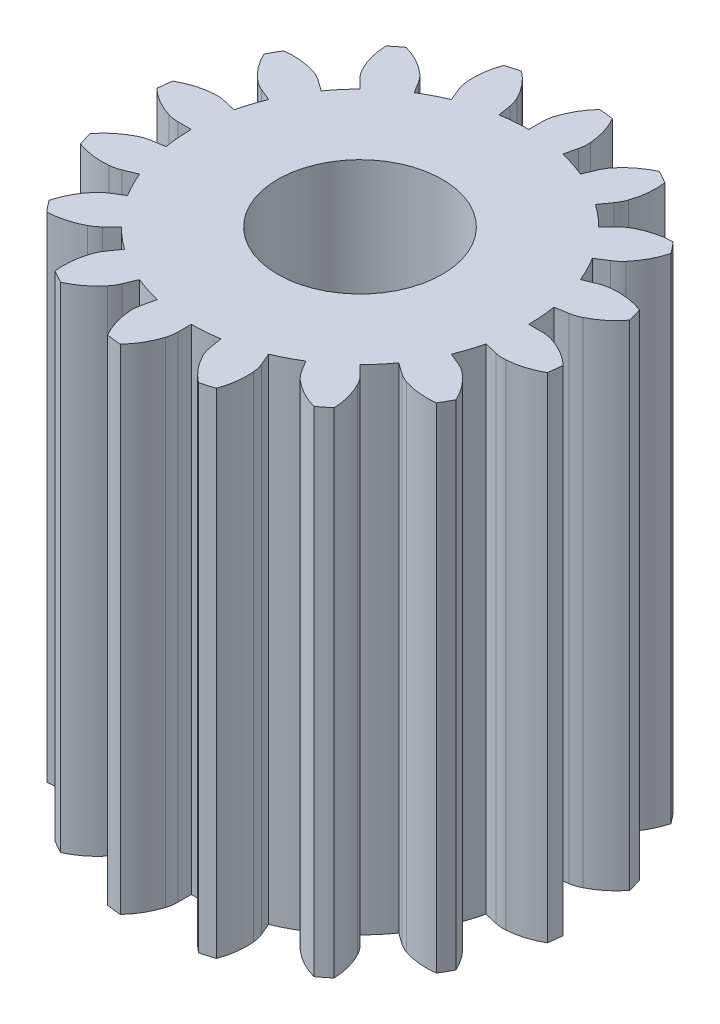
SolidWorks part; units mm, degrees
material "Latão"
ref_plane "Plano frontal" through (0, 0, 0) normal (0, 0, 1) x (1, 0, 0)
ref_plane "Plano superior" through (0, 0, 0) normal (0, 1, 0) x (1, 0, 0)
ref_plane "Plano direito" through (0, 0, 0) normal (1, 0, 0) x (0, 0, -1)
sketch "Esboço5" plane through (0, 0, 0) normal (0, 1, 0) x (1, 0, 0)
  line L0 (0, 0) -> (0, 50000) construction
  line L1 (0, 0) -> (-50000, 0) construction
  line L2 (0, 2.05) -> (0, 2.2117)
  line L3 (0, 0) -> (0.3089, 2.6823) construction
  line L4 (0.4659, 1.9964) -> (0.5027, 2.1538)
  arc A0 (-2.7, 0) -> (2.7, 0) centre (0, 0) ccw
  arc A1 (0, 2.05) -> (0.4659, 1.9964) centre (0, 0) ccw
  arc A2 (-2.4, 0) -> (2.4, 0) centre (0, 0) ccw construction
  arc A3 (-2.255, 0) -> (2.255, 0) centre (0, 0) ccw construction
  arc A4 (0, 2.2117) -> (0.0196, 2.3416) centre (0.44, 2.2117) cw
  arc A5 (0.0196, 2.3416) -> (0.2217, 2.6909) centre (0.8846, 2.0743) cw
  arc A6 (0.5027, 2.1538) -> (0.5131, 2.2848) centre (0.0742, 2.2538) ccw
  arc A7 (0.5131, 2.2848) -> (0.3957, 2.6709) centre (-0.39, 2.221) ccw
  arc A8 (0.3957, 2.6709) -> (0.2217, 2.6909) centre (0, 0) ccw
  arc A9 (0.5067, 2.3459) -> (0, 2.4) centre (0, 0) ccw construction
  arc A10 (0.5104, 2.1965) -> (0, 2.255) centre (0, 0) ccw construction
  point P23 (0.0398, 2.3997)
  point P24 (0.5067, 2.3459)
  dimension "D1" = 5.4
  dimension "D2" = 4.8
  dimension "D3" = 4.51
  dimension "D4" = 4.1
  dimension "D5" = 0.44
  dimension "D6" = 0.9053
  dimension "D7" = 0.47
extrude "Ressalto-extrusão2" add sketch "Esboço5" along normal blind 6 contours A7 A8 A5 A4 L2 A1 L4 A6
pattern_circular "PadrãoCircular1" count 16 every 22.5 about axis through (0, 0, 0) along (0, 1, 0) of "Ressalto-extrusão2"
sketch "Esboço6" plane through (0, 6, 0) normal (0, 1, 0) x (1, 0, 0)
  circle A0 centre (0, 0) radius 1
  dimension "D1" = 2
extrude "Corte-extrusão2" cut sketch "Esboço6" against normal up to surface (6 mm away) up to face at (0, 0, 0)
equation "\"z\"= 16'numero dentes"
equation "\"m\"= 0.3'módulo"
equation "\"dp\"= \"z\" * \"m\"'diametro primitivo"
equation "\"p\"= \"m\" * pi'passo"
equation "\"de\"= \"m\" * ( \"z\" + 2 )'diametro externo"
equation "\"di\"= \"m\" * ( \"z\" - 2.334 )'diametro interno"
equation "\"teta\"= 20'angulo de pressão(geralemente 20)"
equation "\"db\"= \"dp\" * cos ( \"teta\" )'diametro de base"
equation "\"f\"= 2.92'OLHAR ODONTÓGRAFO DE GRANT"
equation "\"f1\"= 1.46'OLHAR ODONTÓGRAFO DE GRANT"
equation "\"r\"= \"m\" * \"f\"'OLHAR ODONTÓGRAFO DE GRANT"
equation "\"r1\"= \"m\" * \"f1\"'OLHAR ODONTÓGRAFO DE GRANT"
